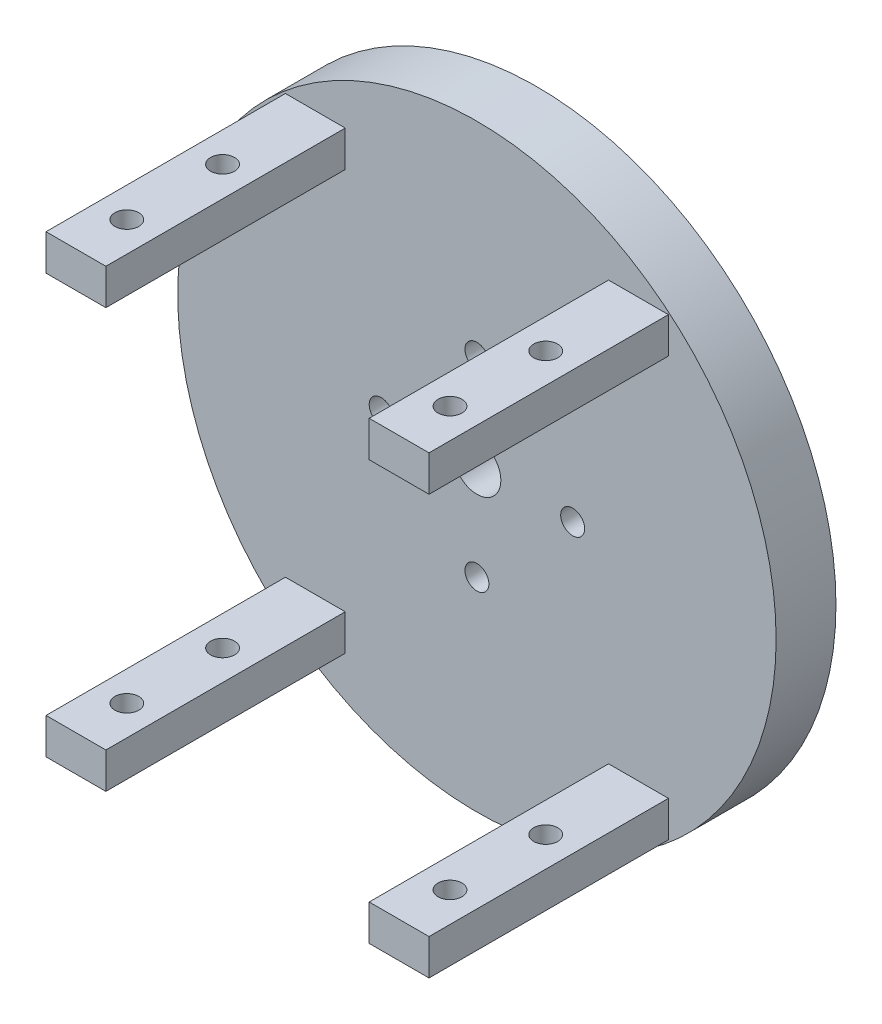
SolidWorks part; units mm, degrees
ref_plane "Front Plane" through (0, 0, 0) normal (0, 0, 1) x (1, 0, 0)
ref_plane "Top Plane" through (0, 0, 0) normal (0, 1, 0) x (1, 0, 0)
ref_plane "Right Plane" through (0, 0, 0) normal (1, 0, 0) x (0, 0, -1)
sketch "Sketch1" plane through (0, 0, 0) normal (0, 0, 1) x (1, 0, 0)
  line L0 (0, 0) -> (0, 8) construction
  circle A0 centre (0, 0) radius 25
  circle A1 centre (0, 8) radius 1
  circle A2 centre (8, 0) radius 1
  circle A3 centre (0, -8) radius 1
  circle A4 centre (-8, 0) radius 1
  circle A5 centre (0, 0) radius 2
  dimension "D1" = 50
  dimension "D2" = 2
  dimension "D3" = 4
  dimension "D5" = 8
  dimension "D4" = 4
extrude "Boss-Extrude1" add sketch "Sketch1" along normal blind 5
sketch "Sketch2" plane through (0, 0, 5) normal (0, 0, 1) x (1, 0, 0)
  line L0 (-11, 19) -> (-16, 19)
  line L1 (-11, 19) -> (11, 19) construction
  line L2 (-11, 19) -> (-11, 16)
  line L3 (-11, -19) -> (11, -19) construction
  line L4 (11, 19) -> (11, 16)
  line L5 (-11, 19) -> (11, -19) construction
  line L6 (-11, -19) -> (11, 19) construction
  line L7 (-16, 19) -> (-16, 16)
  line L8 (-16, -19) -> (-11, -19)
  line L9 (11, -19) -> (16, -19)
  line L10 (16, -19) -> (16, -16)
  line L11 (16, 19) -> (11, 19)
  line L12 (-16, 16) -> (-11, 16)
  line L13 (-16, -16) -> (-11, -16)
  line L14 (11, -16) -> (16, -16)
  line L15 (11, 16) -> (16, 16)
  line L16 (-16, -16) -> (-16, -19)
  line L17 (-11, -16) -> (-11, -19)
  line L18 (11, -16) -> (11, -19)
  line L19 (16, 16) -> (16, 19)
  point P0 (0, 0)
  dimension "D1" = 22
  dimension "D2" = 38
  dimension "D3" = 5
  dimension "D4" = 5
  dimension "D5" = 3
  dimension "D6" = 3
extrude "Boss-Extrude2" add sketch "Sketch2" along normal blind 20
sketch "Sketch3" plane through (0, -19, 0) normal (0, -1, 0) x (1, 0, 0)
  line L0 (-11, 5) -> (11, 5) construction
  circle A0 centre (-13.5, 20.75) radius 1
  circle A1 centre (-13.5, 12.75) radius 1
  circle A2 centre (13.5, 20.75) radius 1
  circle A3 centre (13.5, 12.75) radius 1
  dimension "D1" = 2
  dimension "D2" = 27
  dimension "D3" = 13.5
  dimension "D4" = 7.75
  dimension "D5" = 8
extrude "Cut-Extrude1" cut sketch "Sketch3" against normal through all
